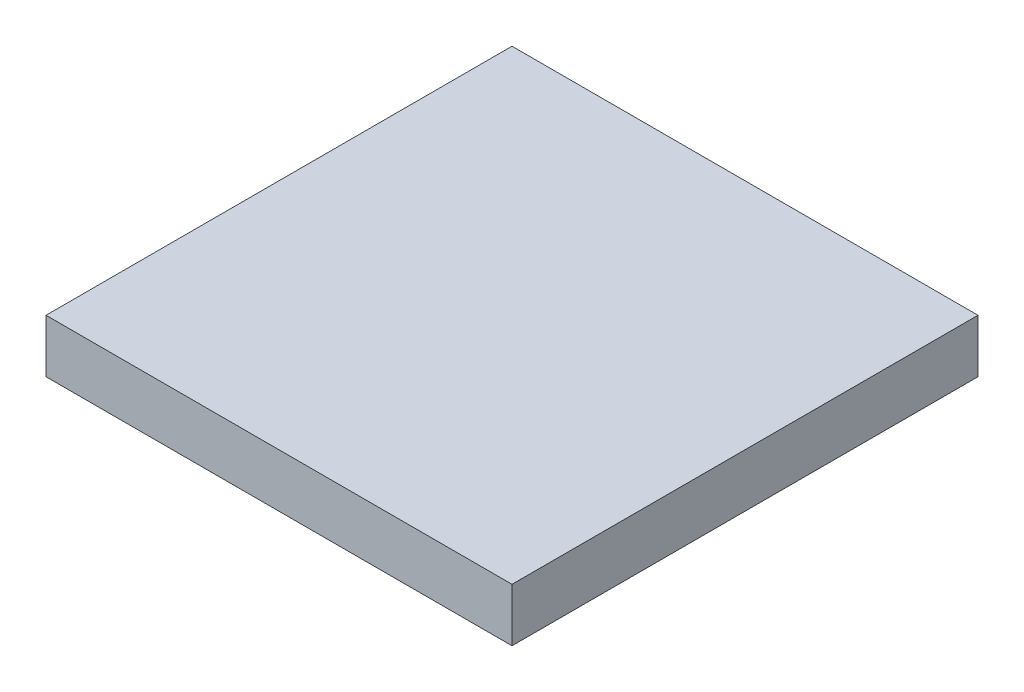
SolidWorks part; units mm, degrees
ref_plane "Front Plane" through (0, 0, 0) normal (0, 0, 1) x (1, 0, 0)
ref_plane "Top Plane" through (0, 0, 0) normal (0, 1, 0) x (1, 0, 0)
ref_plane "Right Plane" through (0, 0, 0) normal (1, 0, 0) x (0, 0, -1)
sketch "Sketch1" plane through (0, 0, 0) normal (0, 1, 0) x (1, 0, 0)
  line L1 (-25.5294, 13.451) -> (-8.0294, 13.451)
  line L2 (-25.5294, 13.451) -> (-25.5294, -4.049)
  line L3 (-25.5294, -4.049) -> (-8.0294, -4.049)
  line L4 (-8.0294, 13.451) -> (-8.0294, -4.049)
  dimension "D1" = 17.5
  dimension "D2" = 17.5
extrude "Boss-Extrude1" add sketch "Sketch1" along normal blind 2
